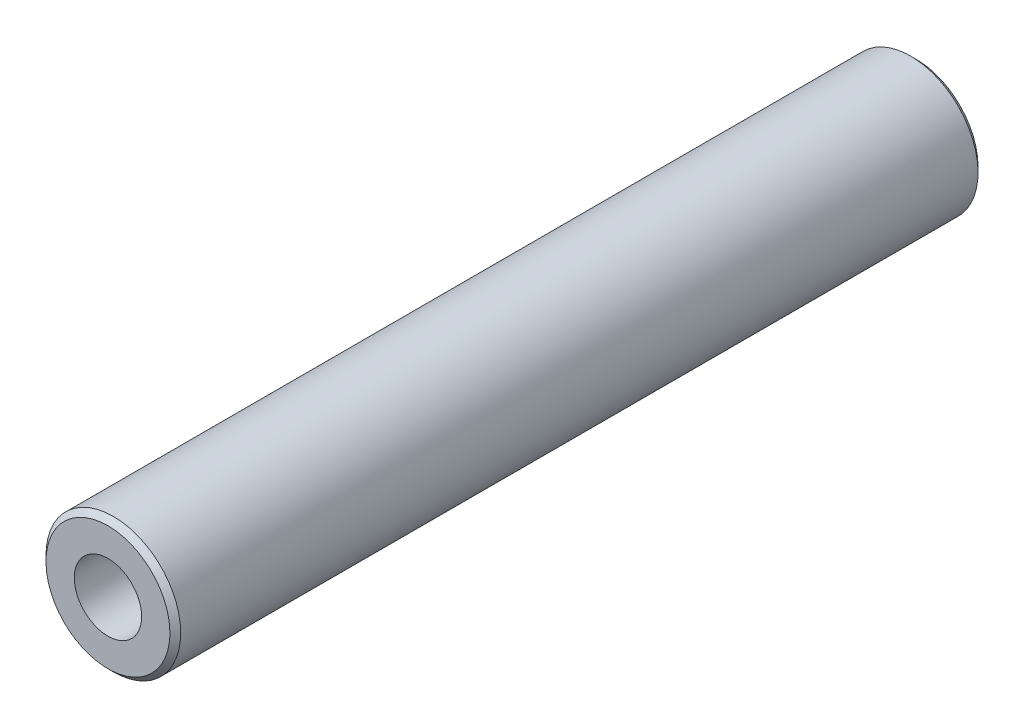
SolidWorks part; units mm, degrees
material "AISI 304"
ref_plane "前视基准面" through (0, 0, 0) normal (0, 0, 1) x (1, 0, 0)
ref_plane "上视基准面" through (0, 0, 0) normal (0, 1, 0) x (1, 0, 0)
ref_plane "右视基准面" through (0, 0, 0) normal (1, 0, 0) x (0, 0, -1)
sketch "草图1" plane through (0, 0, 0) normal (1, 0, 0) x (0, 0, -1)
  line L0 (-15, 0) -> (15, 0) construction
  line L1 (15, 0) -> (15, 2.5)
  line L2 (15, 2.5) -> (-15, 2.5)
  line L3 (-15, 2.5) -> (-15, 0)
  line L4 (15, 0) -> (-15, 0)
  point P4 (0, 0)
  dimension "不锈钢柱大经" = 5
  dimension "不锈钢柱长度" = 30
revolve "旋转1" add sketch "草图1" angle 360 about L0
hole_wizard " 螺纹孔1" positions "草图2" profile "草图3" tap size "M3" standard "GB"
sketch "草图2" plane through (0, 0, 15) normal (0, 0, 1) x (1, 0, 0)
  point P0 (0, 0)
sketch "草图3" plane through (0, 0, 15) normal (1, 0, 0) x (0, -1, 0)
  line L0 (0, 0) -> (0, 14.2511)
  line L1 (0, 14.2511) -> (1.25, 13.5)
  line L2 (1.25, 13.5) -> (1.25, 0)
  line L5 (1.25, 0) -> (0, 0)
  line L10 (0, 14.2511) -> (-1.25, 13.5) construction
  line L11 (0, -6.35) -> (0, 107.95) construction
  dimension "螺纹孔钻头直径" = 2.5
  dimension "螺纹孔钻头深度" = 13.5
  dimension "导头角度" = 118
cosmetic thread "孔螺蚊线1" parameters "D1"=12, "D2"=3.7
mirror "镜向1" about plane through (0, 0, 0) normal (0, 0, 1) of " 螺纹孔1"
cosmetic thread "孔螺蚊线2" parameters "D1"=12, "D2"=3.7
chamfer "倒角1" distance 0.2 angle 45 2 edges at (0, -2.5, -15) (0, -2.5, 15)
